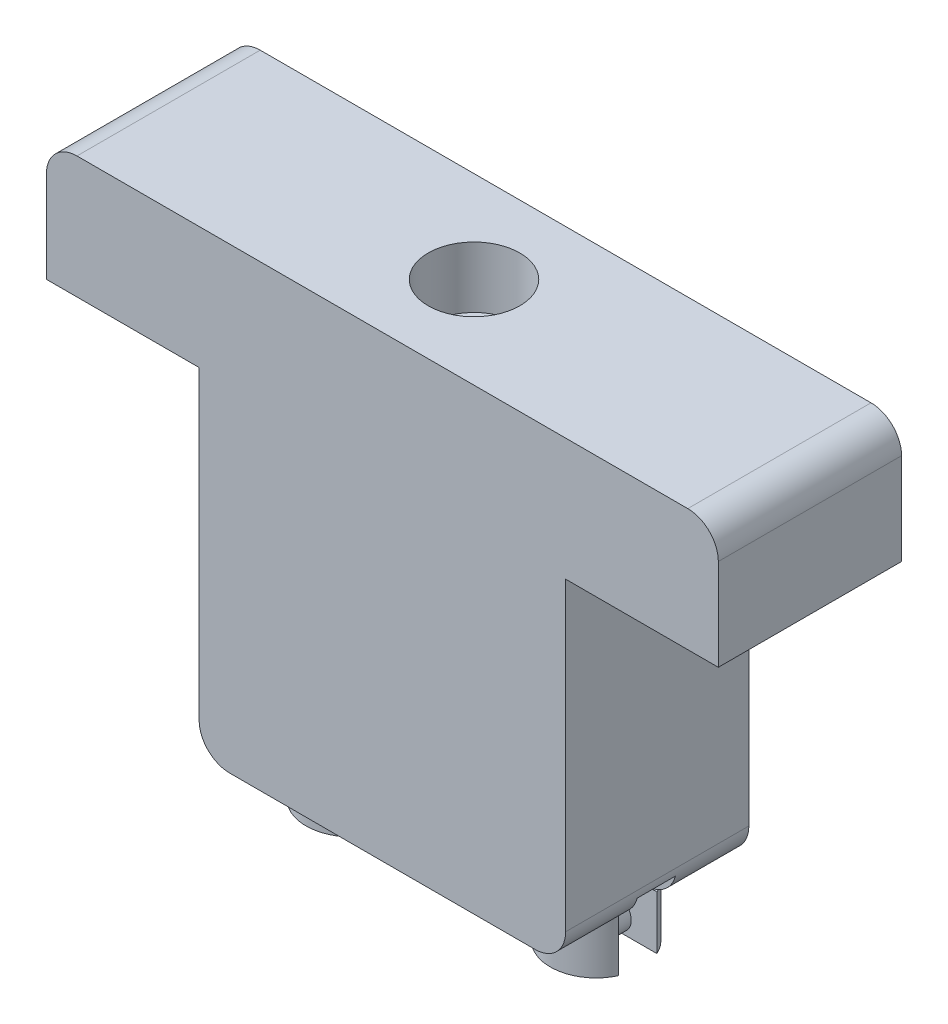
SolidWorks part; units mm, degrees
ref_plane "Front Plane" through (0, 0, 0) normal (0, 0, 1) x (1, 0, 0)
ref_plane "Top Plane" through (0, 0, 0) normal (0, 1, 0) x (1, 0, 0)
ref_plane "Right Plane" through (0, 0, 0) normal (1, 0, 0) x (0, 0, -1)
sketch "Sketch1" plane through (0, 0, 0) normal (0, 0, 1) x (1, 0, 0)
  line L1 (-152.4, -190.5) -> (152.4, -190.5)
  line L2 (-152.4, -190.5) -> (-152.4, 190.5)
  line L3 (-152.4, 190.5) -> (152.4, 190.5)
  line L4 (152.4, -190.5) -> (152.4, 190.5)
  line L5 (-152.4, -190.5) -> (152.4, 190.5) construction
  line L6 (-152.4, 190.5) -> (152.4, -190.5) construction
  point P0 (0, 0)
extrude "Boss-Extrude1" add sketch "Sketch1" along normal blind 152.4 contours L2 L3 L4 L1
sketch "Sketch2" plane through (0, 190.5, 0) normal (0, 1, 0) x (1, 0, 0)
  circle A0 centre (0, -76.2) radius 38.1
extrude "Cut-Extrude1" cut sketch "Sketch2" against normal blind 50.8 contours A0
sketch "Sketch3" plane through (0, -190.5, 0) normal (0, -1, 0) x (1, 0, 0)
  line L1 (-152.4, 152.4) -> (-152.4, 0) construction
  line L2 (152.4, 152.4) -> (152.4, 0) construction
  circle A0 centre (-101.6, 76.2) radius 38.1
  circle A1 centre (101.6, 76.2) radius 38.1
  dimension "D1" = 50.8
  dimension "D2" = 50.8
sketch "Sketch5" plane through (152.4, 0, 0) normal (1, 0, 0) x (0, 0, -1)
  line L0 (0, -190.5) -> (0, 190.5) construction
  line L1 (-152.4, 190.5) -> (0, 190.5)
  line L2 (-152.4, 190.5) -> (-152.4, 88.9)
  line L3 (-152.4, 88.9) -> (0, 88.9)
  line L4 (0, 190.5) -> (0, 88.9)
  dimension "D1" = 101.6
extrude "Boss-Extrude3" add sketch "Sketch5" along normal blind 127
mirror "Mirror1" about plane through (0, 0, 0) normal (1, 0, 0) of "Boss-Extrude3"
sketch "Sketch6" plane through (0, 88.9, 0) normal (0, -1, 0) x (1, 0, 0)
  line L0 (152.4, 152.4) -> (152.4, 0) construction
  circle A2 centre (228.6, 76.2) radius 25.4
  dimension "D1" = 76.2
extrude "Cut-Extrude4" cut sketch "Sketch6" against normal blind 50.8 contours A2
fillet "Fillet4" radius 25.4 2 edges at (-279.4, 190.5, 76.2) (279.4, 190.5, 76.2)
fillet "Fillet5" radius 25.4 2 edges at (152.4, -190.5, 76.2) (-152.4, -190.5, 76.2)
mirror "Mirror2" about plane through (0, 0, 0) normal (1, 0, 0) of "Cut-Extrude4"
extrude "Boss-Extrude4" add sketch "Sketch3" along normal blind 44.45
sketch "Sketch8" plane through (0, -234.95, 0) normal (0, -1, 0) x (1, 0, 0)
  line L1 (40.1643, 60.325) -> (163.0357, 60.325)
  line L2 (40.1643, 60.325) -> (40.1643, 92.075)
  line L3 (40.1643, 92.075) -> (163.0357, 92.075)
  line L4 (163.0357, 60.325) -> (163.0357, 92.075)
  line L5 (40.1643, 60.325) -> (163.0357, 92.075) construction
  line L6 (40.1643, 92.075) -> (163.0357, 60.325) construction
  point P0 (101.6, 76.2)
  dimension "D1" = 31.75
extrude "Cut-Extrude5" cut sketch "Sketch8" against normal blind 63.5
mirror "Mirror3" about plane through (0, 0, 0) normal (1, 0, 0) of "Cut-Extrude5"
sketch "Sketch9" plane through (0, 0, 60.325) normal (0, 0, 1) x (1, 0, 0)
  circle A0 centre (102.2033, -221.697) radius 12.7
extrude "Boss-Extrude5" add sketch "Sketch9" along normal blind 32.766 contours A0
mirror "Mirror4" about plane through (0, 0, 0) normal (1, 0, 0) of "Boss-Extrude5"
